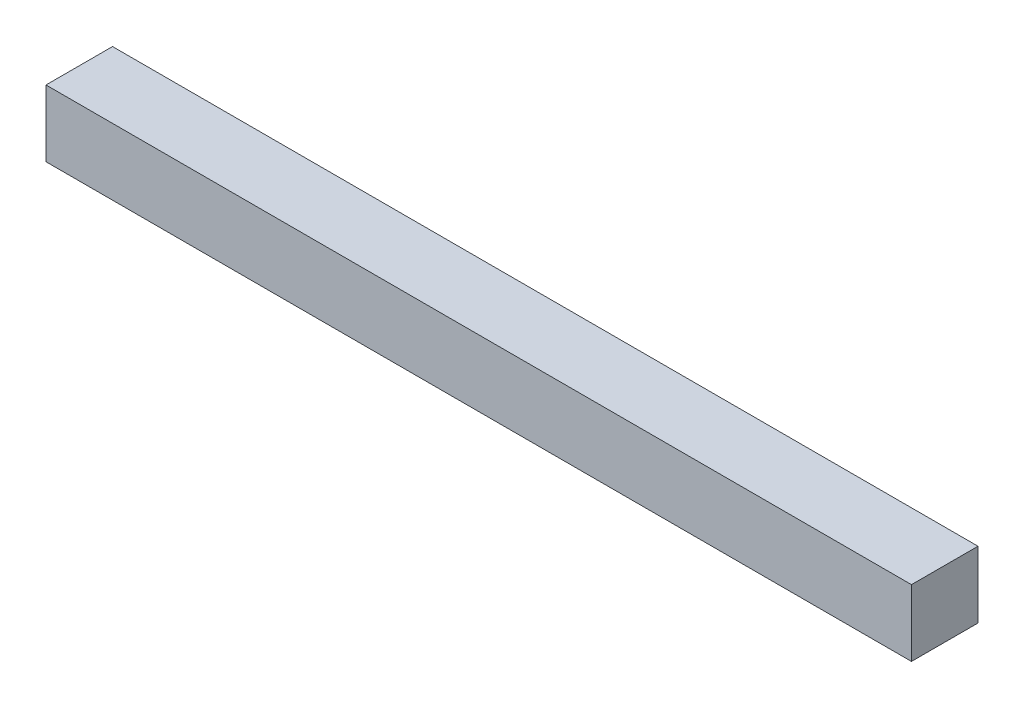
SolidWorks part; units mm, degrees
ref_plane "前视" through (0, 0, 0) normal (0, 0, 1) x (1, 0, 0)
ref_plane "上视" through (0, 0, 0) normal (0, 1, 0) x (1, 0, 0)
ref_plane "右视" through (0, 0, 0) normal (1, 0, 0) x (0, 0, -1)
sketch "草图1" plane through (0, 0, 0) normal (0, 0, 1) x (1, 0, 0)
  line L1 (0, 123) -> (1600, 123)
  line L2 (0, 123) -> (0, 0)
  line L3 (0, 0) -> (1600, 0)
  line L4 (1600, 123) -> (1600, 0)
  dimension "D1" = 1600
  dimension "D2" = 123
extrude "基体-拉伸" add sketch "草图1" along normal blind 123
